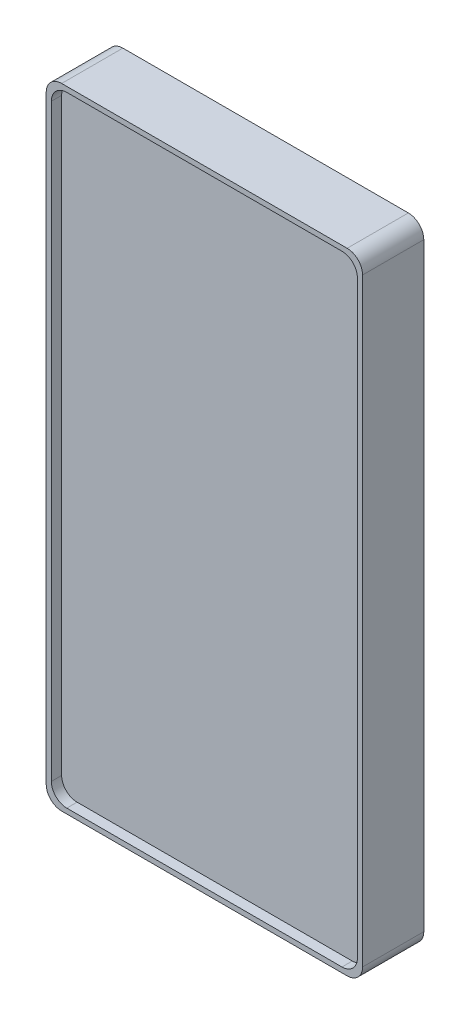
SolidWorks part; units mm, degrees
ref_plane "정면" through (0, 0, 0) normal (0, 0, 1) x (1, 0, 0)
ref_plane "윗면" through (0, 0, 0) normal (0, 1, 0) x (1, 0, 0)
ref_plane "우측면" through (0, 0, 0) normal (1, 0, 0) x (0, 0, -1)
sketch "스케치1" plane through (0, 0, 0) normal (0, 0, 1) x (1, 0, 0)
  line L1 (0, 0) -> (-615, 0)
  line L2 (0, 0) -> (0, 1225)
  line L3 (0, 1225) -> (-615, 1225)
  line L4 (-615, 0) -> (-615, 1225)
  dimension "D1" = 615
  dimension "D2" = 1225
extrude "보스-돌출1" add sketch "스케치1" along normal blind 119
sketch "스케치3" plane through (0, 0, 119) normal (0, 0, 1) x (1, 0, 0)
  line L0 (-615, 0) -> (0, 0) construction
  line L1 (-10, 10) -> (-605, 10)
  line L2 (-10, 10) -> (-10, 1215)
  line L3 (-10, 1215) -> (-605, 1215)
  line L4 (-605, 10) -> (-605, 1215)
  line L5 (-615, 1225) -> (-615, 0) construction
  line L6 (0, 0) -> (0, 1225) construction
  line L7 (0, 1225) -> (-615, 1225) construction
  dimension "D1" = 10
  dimension "D2" = 10
  dimension "D3" = 10
  dimension "D4" = 10
extrude "컷-돌출1" cut sketch "스케치3" against normal blind 20
fillet "필렛3" radius 30 8 edges at (-10, 1215, 109) (-605, 1215, 109) (-10, 10, 109) (-605, 10, 109) (-615, 1225, 59.5) (0, 1225, 59.5) (0, 0, 59.5) (-615, 0, 59.5)
